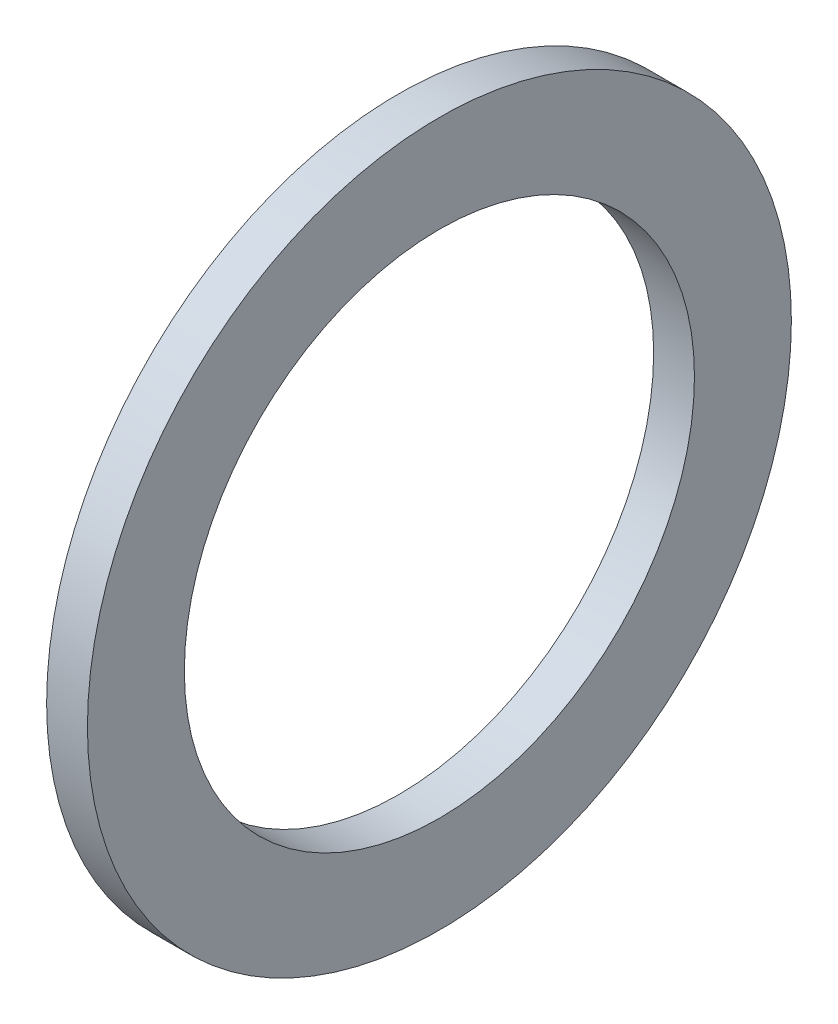
SolidWorks part; units mm, degrees
material "Nylon 101"
ref_plane "Front Plane" through (0, 0, 0) normal (0, 0, 1) x (1, 0, 0)
ref_plane "Top Plane" through (0, 0, 0) normal (0, 1, 0) x (1, 0, 0)
ref_plane "Right Plane" through (0, 0, 0) normal (1, 0, 0) x (0, 0, -1)
sketch "Sketch1" plane through (0, 0, 0) normal (1, 0, 0) x (0, 0, -1)
  circle A0 centre (0, 0) radius 8.763
  circle A1 centre (0, 0) radius 6.35
  dimension "D1" = 17.526
  dimension "D2" = 12.7
extrude "Boss-Extrude1" add sketch "Sketch1" along normal blind 1.016
